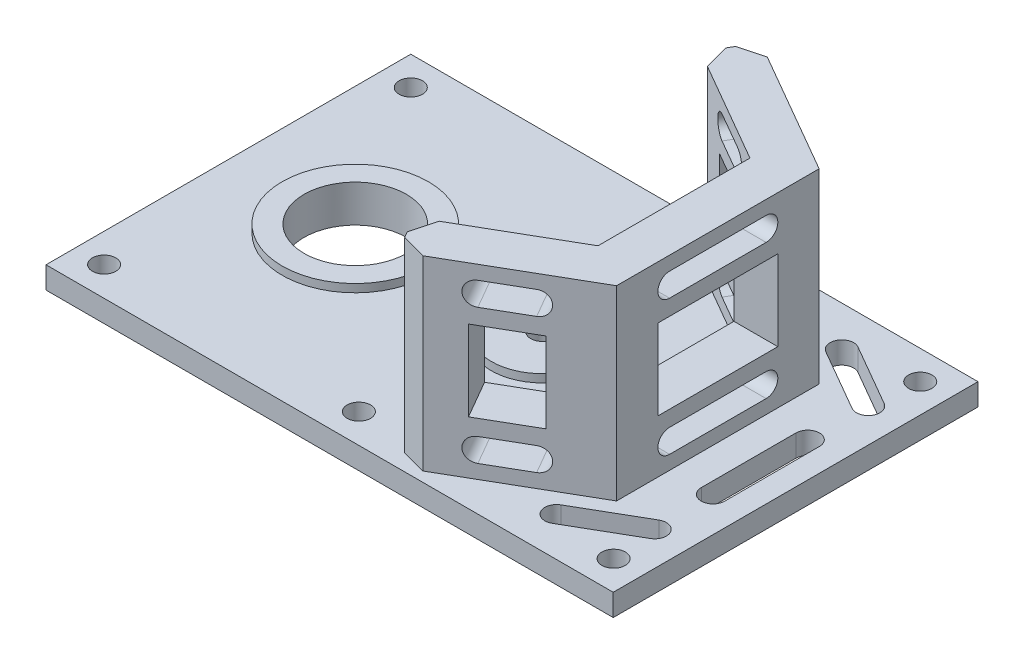
SolidWorks part; units mm, degrees
ref_plane "Front Plane" through (0, 0, 0) normal (0, 0, 1) x (1, 0, 0)
ref_plane "Top Plane" through (0, 0, 0) normal (0, 1, 0) x (1, 0, 0)
ref_plane "Right Plane" through (0, 0, 0) normal (1, 0, 0) x (0, 0, -1)
sketch "Sketch1" plane through (0, 0, 0) normal (0, 1, 0) x (1, 0, 0)
  line L0 (0, 0) -> (-50000, 0) construction
  line L1 (-50, -24.9) -> (27.5936, -24.9)
  line L2 (-50, -24.9) -> (-50, 25)
  line L3 (-50, 25) -> (27.5936, 25)
  line L4 (27.5936, -24.9) -> (27.5936, 25)
  line L5 (-11.2032, 25) -> (-11.2032, -24.9) construction
  circle A0 centre (-32.5938, 0) radius 7
  circle A1 centre (-46.05, 21.05) radius 1.6
  circle A2 centre (-46.05, -20.9) radius 1.6
  circle A3 centre (23.6436, -20.9) radius 1.6
  circle A4 centre (23.6436, 21.05) radius 1.6
  circle A5 centre (-11.2032, -20.9) radius 1.6
  circle A6 centre (-11.2032, 21.05) radius 1.6
  point P0 (0, 0)
  dimension "D3" = 14
  dimension "D6" = 3.2
  dimension "D1" = 49.9
  dimension "D2" = 25
  dimension "D4" = 17.4062
  dimension "D5" = 24.9
  dimension "D7" = 4
  dimension "D8" = 3.95
  dimension "D9" = 3.95
  dimension "D10" = 3.95
  dimension "D11" = 77.5936
extrude "Boss-Extrude6" add sketch "Sketch1" along normal blind 3
sketch "Sketch7" plane through (0, 3, 0) normal (0, 1, 0) x (1, 0, 0)
  line L0 (-32.5938, 0) -> (49967.4062, 0) construction
  circle A0 centre (-32.5938, 0) radius 7
  circle A1 centre (-32.5938, 0) radius 10
  circle A2 centre (-6.9938, 0) radius 7
  dimension "D2" = 25.6
  dimension "D3" = 14
  dimension "D1" = 3
extrude "Boss-Extrude7" add sketch "Sketch7" along normal blind 1.1
sketch "Sketch9" plane through (0, 0, 0) normal (0, -1, 0) x (1, 0, 0)
  circle A0 centre (-32.5938, 0) radius 7
  circle A1 centre (-32.5938, 0) radius 10
  dimension "D1" = 3
extrude "Boss-Extrude9" add sketch "Sketch9" along normal blind 1
sketch "Sketch8" plane through (0, 4.1, 0) normal (0, 1, 0) x (1, 0, 0)
  circle A0 centre (-6.9938, 0) radius 1.5
  dimension "D1" = 3
extrude "Boss-Extrude8" add sketch "Sketch8" along normal blind 0.1 contours A0
sketch "Sketch10" plane through (0, 3, 0) normal (0, 1, 0) x (1, 0, 0)
  line L0 (-7.5938, 0) -> (49992.4062, 0) construction
  line L1 (11.0062, 10.3923) -> (-4.9509, 19.6051)
  line L2 (-21.6399, -11.6159) -> (-4.9509, -19.6051) construction
  line L3 (-4.6894, -26.3824) -> (17.0062, -13.8564) construction
  line L5 (-4.9509, -19.6051) -> (11.0062, -10.3923)
  line L6 (11.0062, -10.3923) -> (11.0062, 10.3923)
  line L7 (17.0062, -13.8564) -> (17.0062, 13.8564)
  line L8 (17.0062, 13.8564) -> (-1.9509, 24.8013)
  line L9 (17.0062, 13.8564) -> (-5.0812, 26.6086) construction
  line L12 (-1.9509, -24.8013) -> (17.0062, -13.8564)
  line L13 (-4.9509, 19.6051) -> (-1.9509, 24.8013)
  line L14 (-4.9509, -19.6051) -> (-1.9509, -24.8013)
  line L15 (-4.9509, 19.6051) -> (-21.1847, 9.409) construction
  line L16 (-5.0812, 26.6086) -> (-27.1133, 12.7707) construction
  line L17 (-12.4881, 17.6125) -> (-21.7129, 12.2866) [skipped]
  line L18 (-21.1847, 9.409) -> (-21.6399, -11.6159) construction
  line L19 (-27.1133, 12.7707) -> (-27.7223, -15.3563) construction
  line L20 (-24.9938, 4.0481) -> (-24.9938, -6.6038) [skipped]
  line L21 (-27.7223, -15.3563) -> (-4.6894, -26.3824) construction
  line L22 (-19.4996, -13.5644) -> (-10.2748, -18.8904) [skipped]
  circle A0 centre (-6.9938, 0) radius 18 construction
  point P1 (11.0062, 0)
  dimension "D2" = 36
  dimension "D1" = 6
extrude "Boss-Extrude10" add sketch "Sketch10" along normal blind 25.5
sketch "Sketch11" plane through (10.2515, 0, 17.7562) normal (0.5, 0, 0.866) x (0.866, 0, -0.5)
  line L0 (-14.0902, 28.5) -> (7.7996, 28.5) construction
  line L2 (-14.0902, 28.5) -> (-14.0902, 3) construction
  line L3 (7.7996, 28.5) -> (7.7996, 3) construction
  line L4 (-14.0902, 3) -> (7.7996, 3) construction
  line L5 (-6.0902, 26.6) -> (-0.2004, 26.6)
  line L6 (-0.2004, 23.4) -> (-6.0902, 23.4)
  line L7 (-6.0902, 8.1) -> (-0.2004, 8.1)
  line L8 (-0.2004, 4.9) -> (-6.0902, 4.9)
  line L9 (-3.1453, 23.4) -> (-3.1453, 8.1) construction
  line L11 (-7.0292, 10.25) -> (0.7386, 10.25)
  line L12 (-7.0292, 10.25) -> (-7.0292, 21.25)
  line L13 (-7.0292, 21.25) -> (0.7386, 21.25)
  line L14 (0.7386, 10.25) -> (0.7386, 21.25)
  line L15 (-7.0292, 10.25) -> (0.7386, 21.25) construction
  line L16 (-7.0292, 21.25) -> (0.7386, 10.25) construction
  arc A0 (-6.0902, 26.6) -> (-6.0902, 23.4) centre (-6.0902, 25) ccw
  arc A1 (-0.2004, 23.4) -> (-0.2004, 26.6) centre (-0.2004, 25) ccw
  arc A2 (-0.2004, 4.9) -> (-0.2004, 8.1) centre (-0.2004, 6.5) ccw
  arc A3 (-6.0902, 8.1) -> (-6.0902, 4.9) centre (-6.0902, 6.5) ccw
  point P1 (-3.1453, 15.75)
  point P7 (-3.1453, 23.4)
  dimension "D1" = 3.2
  dimension "D2" = 3.5
  dimension "D3" = 8
  dimension "D4" = 8
  dimension "D5" = 3.5
  dimension "D6" = 11
extrude "Cut-Extrude3" cut sketch "Sketch11" against normal up to surface (60.0577 mm away)
mirror "Mirror4" about plane through (0, 0, 0) normal (0, 0, 1) of "Cut-Extrude3"
sketch "Sketch12" plane through (0, 4.2, 0) normal (0, 1, 0) x (1, 0, 0)
  circle A0 centre (-6.9938, 0) radius 1.6
  circle A2 centre (-6.9938, 0) radius 1.5 construction
  dimension "D1" = 3.2
sketch "Sketch13" plane through (0, 3, 0) normal (0, 1, 0) x (1, 0, 0)
  line L0 (14.4637, -19.5121) -> (22.9624, -14.6053) construction
  line L1 (13.6612, -18.1221) -> (22.1599, -13.2154)
  line L2 (15.2662, -20.902) -> (23.7649, -15.9953)
  line L3 (-5.3934, -26.7888) -> (43295.8768, 24973.2112) construction
  arc A0 (13.6612, -18.1221) -> (15.2662, -20.902) centre (14.4637, -19.5121) ccw
  arc A1 (23.7649, -15.9953) -> (22.1599, -13.2154) centre (22.9624, -14.6053) ccw
  point P2 (18.713, -17.0587)
  dimension "D1" = 3.21
extrude "Cut-Extrude4" cut sketch "Sketch13" against normal blind 11
mirror "Mirror5" about plane through (0, 0, 0) normal (0, 0, 1) of "Cut-Extrude4"
chamfer "Chamfer2" distance 2.5 angle 45 2 edges at (-4.9509, 15.75, 19.6051) (-4.9509, 15.75, -19.6051)
chamfer "Chamfer3" distance 2.5 angle 45 2 edges at (-1.9509, 15.75, -24.8013) (-1.9509, 15.75, 24.8013)
extrude "Cut-Extrude5" cut sketch "Sketch12" against normal up to surface (4.2 mm away) up to face at (18.713, 0, 17.0587)
sketch "Sketch15" plane through (17.0062, 0, 0) normal (1, 0, 0) x (0, 0, -1)
  line L0 (-1017.8564, 23.4) -> (48982.1436, 23.4) construction
  line L1 (-1017.8564, 4.9) -> (48982.1436, 4.9) construction
  line L2 (-1017.8564, 8.1) -> (48982.1436, 8.1) construction
  line L3 (-1017.3219, 10.25) -> (48982.6781, 10.25) construction
  line L5 (-1017.3219, 21.25) -> (48982.6781, 21.25) construction
  line L6 (-1017.8564, 26.6) -> (48982.1436, 26.6) construction
  line L8 (0, 26.6) -> (0, 4.9) construction
  line L9 (0, 26.6) -> (0, 23.4) construction
  line L10 (-8.2027, 10.25) -> (8.2027, 10.25)
  line L11 (-8.2027, 10.25) -> (-8.2027, 21.25)
  line L12 (-8.2027, 21.25) -> (8.2027, 21.25)
  line L13 (8.2027, 10.25) -> (8.2027, 21.25)
  line L14 (-8.2027, 10.25) -> (8.2027, 21.25) construction
  line L15 (-8.2027, 21.25) -> (8.2027, 10.25) construction
  line L16 (-6.6027, 25) -> (6.6027, 25) construction
  line L17 (-6.6027, 26.6) -> (6.6027, 26.6)
  line L18 (-6.6027, 23.4) -> (6.6027, 23.4)
  line L19 (-1000, 15.75) -> (49000, 15.75) construction
  line L20 (0, 4.9) -> (0, 8.1) construction
  line L21 (-6.6027, 6.5) -> (6.6027, 6.5) construction
  line L22 (-6.6027, 4.9) -> (6.6027, 4.9)
  line L23 (-6.6027, 8.1) -> (6.6027, 8.1)
  arc A0 (-6.6027, 26.6) -> (-6.6027, 23.4) centre (-6.6027, 25) ccw
  arc A1 (6.6027, 23.4) -> (6.6027, 26.6) centre (6.6027, 25) ccw
  arc A2 (-6.6027, 4.9) -> (-6.6027, 8.1) centre (-6.6027, 6.5) cw
  arc A3 (6.6027, 8.1) -> (6.6027, 4.9) centre (6.6027, 6.5) cw
  point P18 (0, 15.75)
  point P29 (0, 25)
  point P38 (0, 6.5)
  point P44 (8.2027, 6.5)
  point P45 (8.2027, 15.75)
extrude "Cut-Extrude6" cut sketch "Sketch15" against normal up to surface (6 mm away) up to face at (11.0062, 15.75, 0)
sketch "Sketch16" plane through (0, 3, 0) normal (0, 1, 0) x (1, 0, 0)
  line L0 (22.8201, -6.4796) -> (22.8201, 6.4796) construction
  line L1 (21.2151, -6.4796) -> (21.2151, 6.4796)
  line L2 (24.4251, -6.4796) -> (24.4251, 6.4796)
  line L3 (0, 0) -> (-50000, 0) construction
  arc A0 (21.2151, -6.4796) -> (24.4251, -6.4796) centre (22.8201, -6.4796) ccw
  arc A1 (24.4251, 6.4796) -> (21.2151, 6.4796) centre (22.8201, 6.4796) ccw
  point P2 (22.8201, 0)
  dimension "D1" = 3.21
extrude "Cut-Extrude7" cut sketch "Sketch16" against normal up to surface (3 mm away) up to face at (-6.9938, 0, -1.6)
